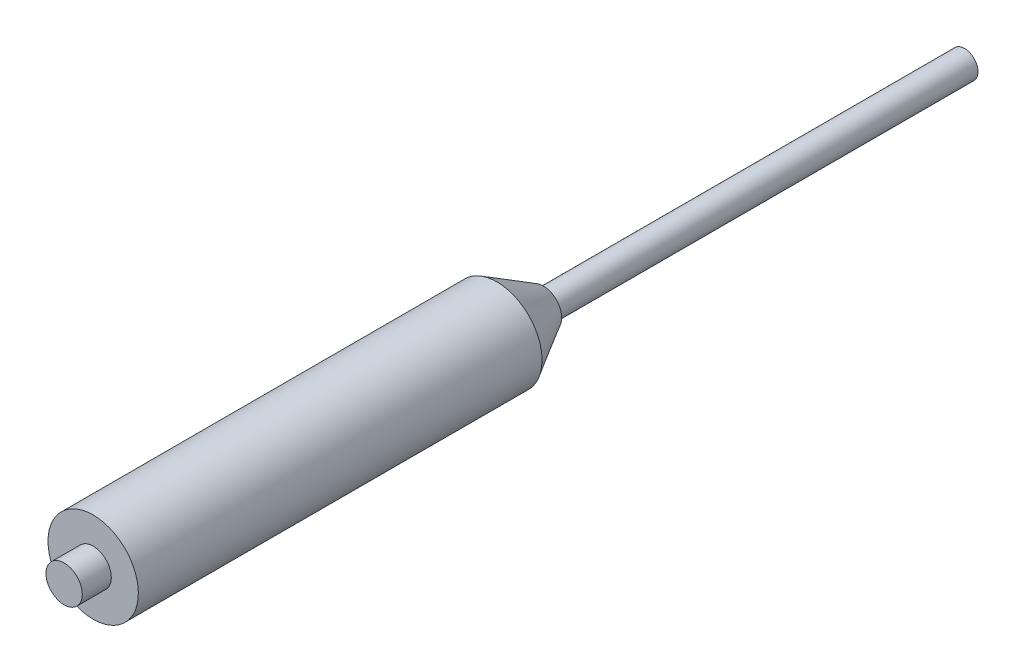
SolidWorks part; units mm, degrees
ref_plane "Front Plane" through (0, 0, 0) normal (0, 0, 1) x (1, 0, 0)
ref_plane "Top Plane" through (0, 0, 0) normal (0, 1, 0) x (1, 0, 0)
ref_plane "Right Plane" through (0, 0, 0) normal (1, 0, 0) x (0, 0, -1)
sketch "Sketch1" plane through (0, 0, 0) normal (0, 0, 1) x (1, 0, 0)
  circle A0 centre (0, 0) radius 3.9497
  dimension "D1" = 7.8994
extrude "Boss-Extrude1" add sketch "Sketch1" along normal blind 78.74
sketch "Sketch2" plane through (0, 0, 78.74) normal (0, 0, 1) x (1, 0, 0)
  circle A0 centre (0, 0) radius 1.5875
  circle A2 centre (0, 0) radius 3.9497 construction
  circle A3 centre (0, 0) radius 3.9497
  dimension "D1" = 3.175
extrude "Cut-Extrude1" cut sketch "Sketch2" against normal blind 2.54
sketch "Sketch4" plane through (0, 0, 0) normal (0, 0, -1) x (-1, 0, 0)
  circle A0 centre (0, 0) radius 1.1811
  circle A1 centre (0, 0) radius 3.9497 construction
  circle A2 centre (0, 0) radius 3.9497
  dimension "D1" = 2.3622
extrude "Cut-Extrude3" cut sketch "Sketch4" against normal blind 36.83
chamfer "Chamfer1" distance 4.064 angle 30 1 edges at (-3.9497, 0, 36.83)
